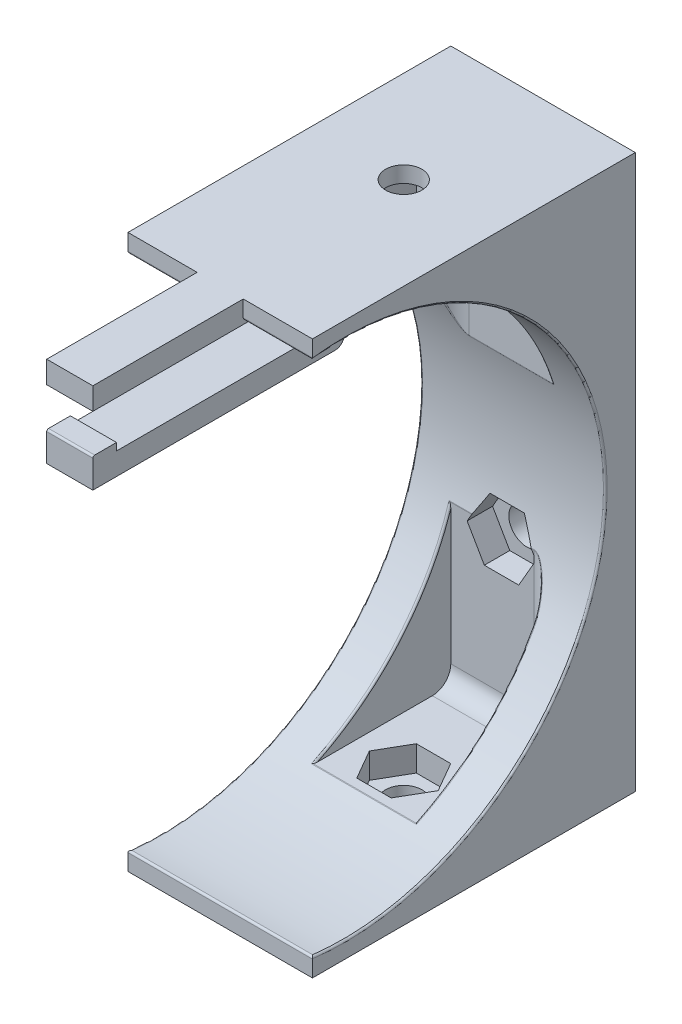
SolidWorks part; units mm, degrees
ref_plane "Front" through (0, 0, 0) normal (0, 0, 1) x (1, 0, 0)
ref_plane "Top" through (0, 0, 0) normal (0, 1, 0) x (1, 0, 0)
ref_plane "Right" through (0, 0, 0) normal (1, 0, 0) x (0, 0, -1)
sketch "Sketch1" plane through (0, 0, 0) normal (0, 0, 1) x (1, 0, 0)
  line L1 (-12.7, 38.1) -> (12.7, 38.1)
  line L2 (-12.7, 38.1) -> (-12.7, -38.1)
  line L3 (-12.7, -38.1) -> (12.7, -38.1)
  line L4 (12.7, 38.1) -> (12.7, -38.1)
  line L5 (-12.7, 38.1) -> (12.7, -38.1) construction
  line L6 (-12.7, -38.1) -> (12.7, 38.1) construction
  point P0 (0, 0)
  dimension "D1" = 25.4
  dimension "D2" = 76.2
extrude "Boss-Extrude1" add sketch "Sketch1" along normal blind 44.45
shell "Shell1" thickness 5.715
sketch "Sketch2" plane through (12.7, 0, 0) normal (1, 0, 0) x (0, 0, -1)
  line L0 (-36.4137, 38.1) -> (-36.4137, -38.1) construction
  line L1 (-44.45, 38.1) -> (0, 38.1) construction
  line L2 (-44.45, -38.1) -> (0, -38.1) construction
  line L7 (0, -38.1) -> (0, 38.1)
  line L8 (0, 38.1) -> (-44.45, 38.1)
  line L9 (-44.45, 38.1) -> (-44.45, -38.1)
  line L10 (-44.45, -38.1) -> (0, -38.1)
  line L11 (0, -38.1) -> (0, 38.1)
  line L12 (0, 38.1) -> (-44.45, 38.1)
  line L13 (-44.45, 38.1) -> (-44.45, -38.1)
  line L14 (-44.45, -38.1) -> (0, -38.1)
  arc A0 (-44.45, 35.56) -> (-44.45, -35.56) centre (-39.9694, 0) cw
  dimension "D2" = 2.54
  dimension "D3" = 2.54
  dimension "D1" = 0
extrude "Cut-Extrude3" cut sketch "Sketch2" against normal through all both contours A0 L0 | L0 A0 L13
sketch "Sketch4" plane through (0, 38.1, 0) normal (0, 1, 0) x (1, 0, 0)
  line L0 (0, -24.4475) -> (0, 24.4475) construction
  line L1 (-13.97, 0) -> (13.97, 0) construction
  circle A0 centre (0, -19.177) radius 2.5
  dimension "D1" = 5
  dimension "D2" = 19.177
extrude "Cut-Extrude4" cut sketch "Sketch4" against normal through all both
sketch "Sketch5" plane through (0, 0, 5.715) normal (0, 0, 1) x (1, 0, 0)
  line L0 (0, -24.4475) -> (0, 24.4475) construction
  line L2 (-12.7, -38.1) -> (12.7, -38.1) construction
  circle A0 centre (0, -11.684) radius 2.5
  dimension "D1" = 5
  dimension "D2" = 26.416
extrude "Cut-Extrude5" cut sketch "Sketch5" against normal through all both
fillet "Fillet1" radius 2.54 2 edges at (0, 32.385, 5.715) (0, -32.385, 5.715)
fillet "Fillet2" radius 0.254 16 edges at (0, 35.56, 44.45) (0, -35.56, 44.45) (-12.7, 0, 4.1282) (12.7, 0, 4.1282) (6.985, -25.8681, 15.1615) (5.0613, -10.7899, 5.7909) (6.985, 23.4535, 12.8673) (0, 32.385, 24.6136) (-6.985, 25.8681, 15.1615) (-5.0613, 10.7899, 5.7909) (-6.985, -23.4535, 12.8673) (0, -32.385, 24.6136) (1.27, 10.5464, 5.715) (3.3356, -10.5464, 5.715) (-4.6056, -10.5464, 5.715) (0.2184, -9.1936, 5.3274)
sketch "Sketch6" plane through (0, 32.385, 0) normal (0, -1, 0) x (1, 0, 0)
  circle A0 centre (0, 19.177) radius 2.5 construction
  circle A1 centre (0, 19.177) radius 2.5
sketch "Sketch7" plane through (0, -32.385, 0) normal (0, 1, 0) x (1, 0, 0)
  line L1 (-2.3671, -23.277) -> (2.3671, -23.277)
  line L2 (2.3671, -23.277) -> (4.7343, -19.177)
  line L3 (4.7343, -19.177) -> (2.3671, -15.077)
  line L4 (2.3671, -15.077) -> (-2.3671, -15.077)
  line L5 (-2.3671, -15.077) -> (-4.7343, -19.177)
  line L6 (-4.7343, -19.177) -> (-2.3671, -23.277)
  circle A0 centre (0, -19.177) radius 2.5 construction
  circle A1 centre (0, -19.177) radius 2.5
  circle A2 centre (0, -19.177) radius 4.1 construction
  dimension "D1" = 8.2
extrude "Cut-Extrude6" cut sketch "Sketch7" against normal blind 3.5
sketch "Sketch8" plane through (0, 0, 5.715) normal (0, 0, 1) x (1, 0, 0)
  line L1 (4.7343, -11.684) -> (2.3671, -7.584)
  line L2 (2.3671, -7.584) -> (-2.3671, -7.584)
  line L3 (-2.3671, -7.584) -> (-4.7343, -11.684)
  line L4 (-4.7343, -11.684) -> (-2.3671, -15.784)
  line L5 (-2.3671, -15.784) -> (2.3671, -15.784)
  line L6 (2.3671, -15.784) -> (4.7343, -11.684)
  circle A0 centre (0, -11.684) radius 2.5 construction
  circle A1 centre (0, -11.684) radius 2.5
  circle A2 centre (0, -11.684) radius 4.1 construction
  dimension "D1" = 8.2
extrude "Cut-Extrude7" cut sketch "Sketch8" against normal blind 3.5
sketch "Sketch9" plane through (0, 32.385, 0) normal (0, -1, 0) x (1, 0, 0)
  line L1 (2.3671, 15.077) -> (4.7343, 19.177)
  line L2 (4.7343, 19.177) -> (2.3671, 23.277)
  line L3 (2.3671, 23.277) -> (-2.3671, 23.277)
  line L4 (-2.3671, 23.277) -> (-4.7343, 19.177)
  line L5 (-4.7343, 19.177) -> (-2.3671, 15.077)
  line L6 (-2.3671, 15.077) -> (2.3671, 15.077)
  circle A0 centre (0, 19.177) radius 2.5 construction
  circle A1 centre (0, 19.177) radius 2.5
  circle A2 centre (0, 19.177) radius 4.1 construction
  dimension "D1" = 8.2
extrude "Cut-Extrude8" cut sketch "Sketch9" against normal blind 3.5
sketch "Sketch10" plane through (0, 0, 0) normal (1, 0, 0) x (0, 0, -1)
  line L1 (-30.5295, 38.1) -> (-65.1574, 38.1)
  line L2 (-30.5295, 38.1) -> (-30.5295, 35.052)
  line L3 (-30.5295, 35.052) -> (-65.1574, 35.052)
  line L4 (-65.1574, 38.1) -> (-65.1574, 35.052)
  line L5 (-44.45, -35.8469) -> (-44.45, -38.1)
  line L6 (-44.45, -38.1) -> (0, -38.1)
  line L7 (0, -38.1) -> (0, 38.1)
  line L8 (0, 38.1) -> (-44.45, 38.1)
  line L9 (-44.45, 38.1) -> (-44.45, 35.8469)
  line L10 (-44.45, -35.8469) -> (-44.45, -38.1)
  line L11 (-44.45, -38.1) -> (0, -38.1)
  line L12 (0, -38.1) -> (0, 38.1)
  line L13 (0, 38.1) -> (-44.45, 38.1)
  line L14 (-44.45, 38.1) -> (-44.45, 35.8469)
  line L15 (-30.5295, 35.052) -> (-33.0695, 35.052)
  line L16 (-30.5295, 35.052) -> (-30.5295, 28.702)
  line L17 (-30.5295, 28.702) -> (-33.0695, 28.702)
  line L18 (-33.0695, 35.052) -> (-33.0695, 28.702)
  line L19 (-30.5295, 28.702) -> (-65.1574, 28.702)
  line L20 (-30.5295, 28.702) -> (-30.5295, 26.924)
  line L21 (-31.7995, 25.654) -> (-65.1574, 25.654)
  line L22 (-65.1574, 28.702) -> (-65.1574, 25.654)
  line L23 (-65.1574, 28.702) -> (-61.9009, 28.702)
  line L24 (-65.1574, 28.702) -> (-65.1574, 29.464)
  line L25 (-64.9034, 29.718) -> (-61.9009, 29.718)
  line L26 (-61.9009, 28.702) -> (-61.9009, 29.718)
  arc A0 (-64.9034, 29.718) -> (-65.1574, 29.464) centre (-64.9034, 29.464) ccw
  arc A1 (-30.5295, 26.924) -> (-31.7995, 25.654) centre (-31.7995, 26.924) cw
  arc A3 (-44.4481, -35.8162) -> (-44.4481, 35.8162) centre (-39.9694, 0) ccw
  arc A4 (-44.4481, -35.8162) -> (-44.45, -35.8469) centre (-44.196, -35.8469) ccw
  arc A5 (-44.45, 35.8469) -> (-44.4481, 35.8162) centre (-44.196, 35.8469) ccw
  arc A6 (-44.4481, -35.8162) -> (-44.4481, 35.8162) centre (-39.9694, 0) ccw
  arc A7 (-44.4481, -35.8162) -> (-44.45, -35.8469) centre (-44.196, -35.8469) ccw
  arc A8 (-44.45, 35.8469) -> (-44.4481, 35.8162) centre (-44.196, 35.8469) ccw
  point P26 (-65.1574, 29.718)
  dimension "D6" = 0.254
  dimension "D8" = 1.27
  dimension "D2" = 3.048
  dimension "D3" = 3.048
  dimension "D4" = 1.016
  dimension "D5" = 6.35
  dimension "D7" = 2.54
  dimension "D1" = 0
extrude "Boss-Extrude2" add sketch "Sketch10" along normal mid plane 6.35 contours L2 L1 L4 L3 | L16 L15 L18 L17 | L20 A1 L21 L22 L19 | L24 A0 L25 L26 L23
